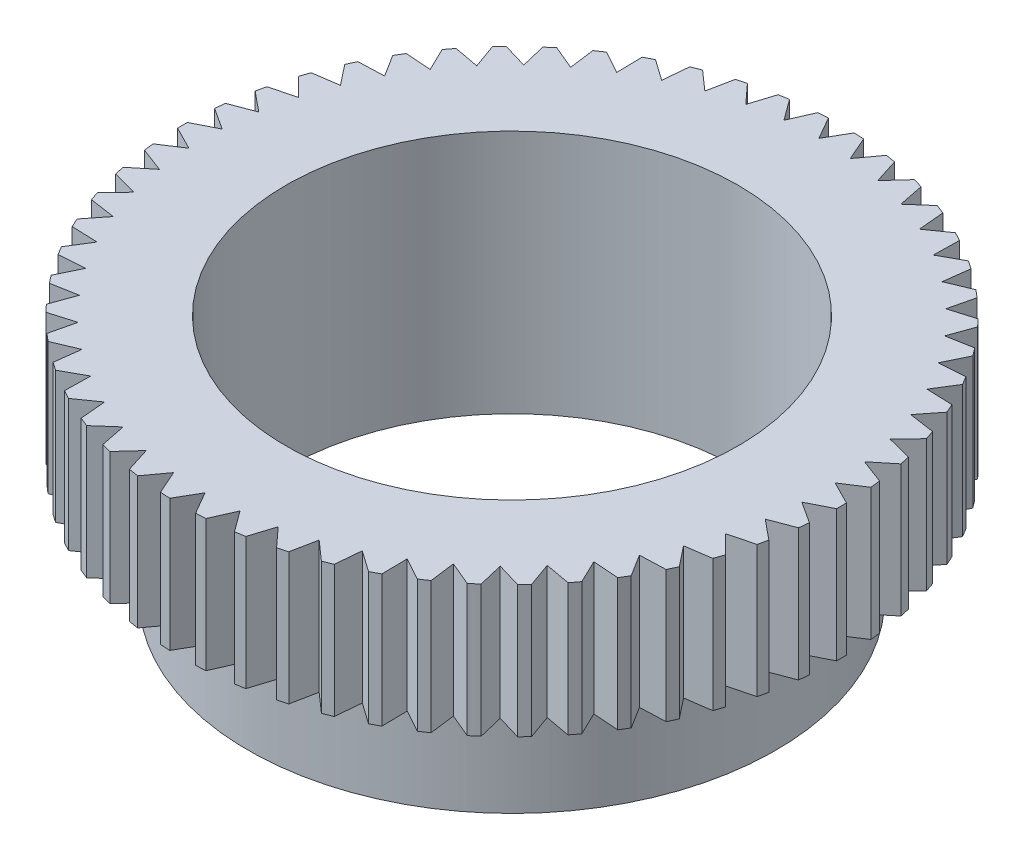
SolidWorks part; units mm, degrees
material "Acier inoxydable chromé"
ref_plane "Plan de face" through (0, 0, 0) normal (0, 0, 1) x (1, 0, 0)
ref_plane "Plan de dessus" through (0, 0, 0) normal (0, 1, 0) x (1, 0, 0)
ref_plane "Plan de droite" through (0, 0, 0) normal (1, 0, 0) x (0, 0, -1)
sketch "Esquisse1" plane through (0, 0, 0) normal (0, 0, 1) x (1, 0, 0)
  line L0 (0, -0.7324) -> (0, 6.7886) construction
  line L1 (-6, 0) -> (-6, 6.5)
  line L4 (-6, 6.5) -> (-8.75, 6.5)
  line L5 (-8.75, 6.5) -> (-8.75, 3)
  line L6 (-8.75, 3) -> (-7, 3)
  line L7 (-7, 3) -> (-7, 0)
  line L8 (-7, 0) -> (-6, 0)
  dimension "D1" = 12
  dimension "D2" = 6.5
  dimension "D3" = 3
  dimension "D4" = 14
  dimension "D5" = 17.5
revolve "Révolution1" add sketch "Esquisse1" angle 360 about L0
sketch "Esquisse2" plane through (0, 6.5, 0) normal (0, 1, 0) x (1, 0, 0)
  line L0 (0, 8.15) -> (0.3464, 8.75)
  line L1 (0.3464, 8.75) -> (-0.3464, 8.75)
  line L2 (-0.3464, 8.75) -> (0, 8.15)
  point P2 (0, 8.75)
  dimension "D1" = 60
  dimension "D2" = 0.6
extrude "Enlèv. mat.-Extru.1" cut sketch "Esquisse2" against normal up to next
pattern_circular "Répétition circulaire1" count 58 over 360 about axis through (0, 0, 0) along (0, 1, 0) of "Enlèv. mat.-Extru.1"
